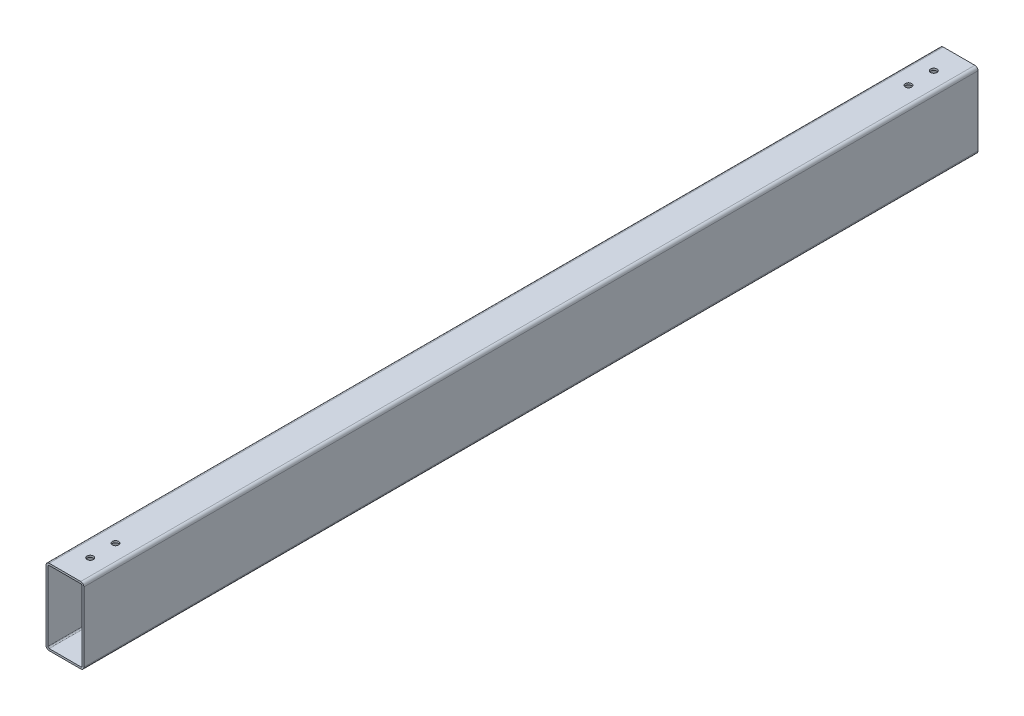
SolidWorks part; units mm, degrees
ref_plane "Front Plane" through (0, 0, 0) normal (0, 0, 1) x (1, 0, 0)
ref_plane "Top Plane" through (0, 0, 0) normal (0, 1, 0) x (1, 0, 0)
ref_plane "Right Plane" through (0, 0, 0) normal (1, 0, 0) x (0, 0, -1)
sketch "Sketch2" plane through (0, 0, 0) normal (0, 0, 1) x (1, 0, 0)
  line L1 (-25, -60) -> (25, -60)
  line L2 (-30, -55) -> (-30, 55)
  line L3 (-25, 60) -> (25, 60)
  line L4 (30, -55) -> (30, 55)
  line L5 (-30, -60) -> (30, 60) construction
  line L6 (-30, 60) -> (30, -60) construction
  arc A0 (-30, 55) -> (-25, 60) centre (-25, 55) cw
  arc A1 (25, 60) -> (30, 55) centre (25, 55) cw
  arc A2 (30, -55) -> (25, -60) centre (25, -55) cw
  arc A3 (-25, -60) -> (-30, -55) centre (-25, -55) cw
  point P0 (0, 0)
  dimension "D3" = 5
  dimension "D1" = 60
  dimension "D2" = 120
extrude "Extrude-Thin1" add sketch "Sketch2" along normal blind 708 and the other way blind 708 thin thin type one direction reverse wall 3
sketch "Sketch3" plane through (0, 60, 0) normal (0, 1, 0) x (1, 0, 0)
  line L0 (25, 708) -> (-25, 708) construction
  line L1 (0, -55) -> (0, 55) construction
  line L2 (-55, 0) -> (55, 0) construction
  circle A0 centre (0, 668) radius 5
  circle A1 centre (0, 628) radius 5
  circle A2 centre (0, -628) radius 5
  circle A3 centre (0, -668) radius 5
  dimension "D3" = 10
  dimension "D1" = 40
  dimension "D2" = 40
extrude "Cut-Extrude1" cut sketch "Sketch3" against normal up to next
